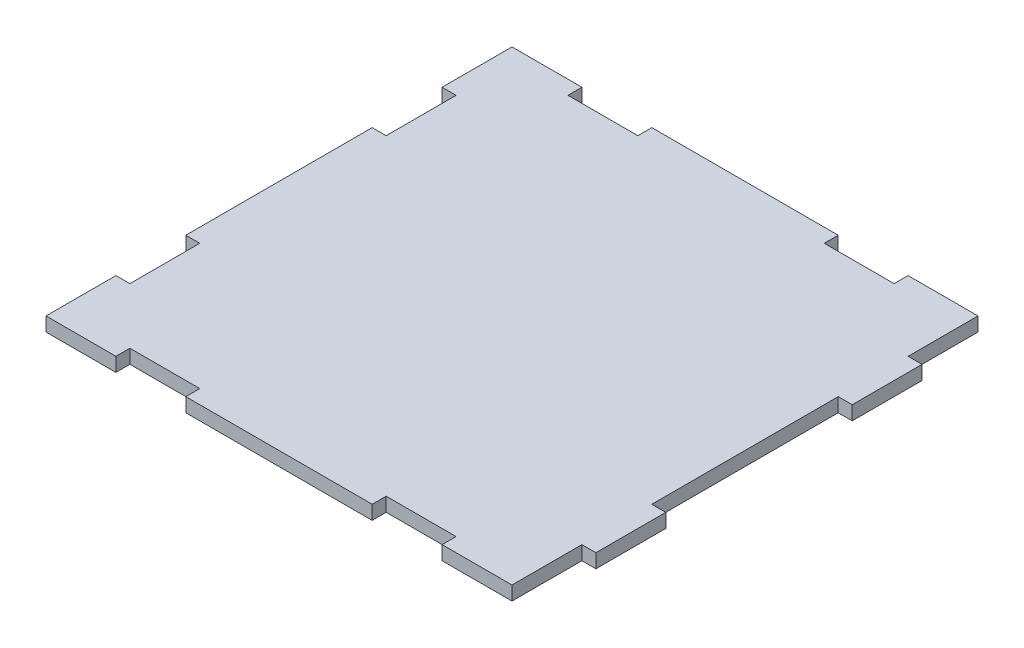
SolidWorks part; units mm, degrees
ref_plane "Plano frontal" through (0, 0, 0) normal (0, 0, 1) x (1, 0, 0)
ref_plane "Plano superior" through (0, 0, 0) normal (0, 1, 0) x (1, 0, 0)
ref_plane "Plano direito" through (0, 0, 0) normal (1, 0, 0) x (0, 0, -1)
sketch "Esboço1" plane through (0, 0, 0) normal (0, 1, 0) x (1, 0, 0)
  line L0 (100, 70) -> (100, 100)
  line L1 (-100, -100) -> (100, -100)
  line L2 (-100, -100) -> (-100, 100)
  line L3 (-100, 100) -> (100, 100)
  line L5 (-100, -100) -> (100, 100) construction
  line L6 (-100, 100) -> (100, -100) construction
  line L7 (100, 70) -> (106, 70)
  line L9 (100, 40) -> (106, 40)
  line L10 (106, 70) -> (106, 40)
  line L11 (100, -40) -> (106, -40)
  line L13 (100, -70) -> (106, -70)
  line L14 (106, -40) -> (106, -70)
  line L15 (100, 40) -> (100, -40)
  line L16 (100, -70) -> (100, -100)
  point P0 (0, 0)
  dimension "D1" = 200
  dimension "D2" = 200
  dimension "D3" = 6
  dimension "D4" = 6
  dimension "D5" = 30
  dimension "D6" = 30
  dimension "D7" = 30
  dimension "D8" = 30
  dimension "D9" = 6
  dimension "D10" = 6
extrude "Ressalto-extrusão1" add sketch "Esboço1" along normal blind 6
sketch "Esboço2" plane through (0, 6, 0) normal (0, 1, 0) x (1, 0, 0)
  line L0 (-100, -100) -> (100, -100) construction
  line L1 (-70, -100) -> (-40, -100)
  line L2 (-70, -100) -> (-70, -94)
  line L3 (-70, -94) -> (-40, -94)
  line L4 (-40, -100) -> (-40, -94)
  line L6 (40, -100) -> (70, -100)
  line L7 (40, -100) -> (40, -94)
  line L8 (40, -94) -> (70, -94)
  line L9 (70, -100) -> (70, -94)
  line L10 (-100, 100) -> (-100, -100) construction
  line L11 (100, 100) -> (-100, 100) construction
  line L12 (-70, 100) -> (-40, 100)
  line L13 (-70, 100) -> (-70, 94)
  line L14 (-70, 94) -> (-40, 94)
  line L15 (-40, 100) -> (-40, 94)
  line L16 (100, 70) -> (100, 100) construction
  line L17 (40, 100) -> (70, 100)
  line L18 (40, 100) -> (40, 94)
  line L19 (40, 94) -> (70, 94)
  line L20 (70, 100) -> (70, 94)
  line L21 (-100, 70) -> (-94, 70)
  line L22 (-100, 70) -> (-100, 40)
  line L23 (-100, 40) -> (-94, 40)
  line L24 (-94, 70) -> (-94, 40)
  line L25 (-100, -40) -> (-94, -40)
  line L26 (-100, -40) -> (-100, -70)
  line L27 (-100, -70) -> (-94, -70)
  line L28 (-94, -40) -> (-94, -70)
  line L29 (100, -100) -> (100, -70) construction
  dimension "D1" = 30
  dimension "D2" = 30
  dimension "D3" = 6
  dimension "D4" = 6
  dimension "D5" = 30
  dimension "D6" = 30
  dimension "D7" = 30
  dimension "D8" = 30
  dimension "D9" = 30
  dimension "D10" = 6
  dimension "D11" = 30
  dimension "D12" = 6
  dimension "D13" = 6
  dimension "D14" = 6
  dimension "D15" = 30
  dimension "D16" = 30
  dimension "D17" = 30
  dimension "D18" = 30
extrude "Corte-extrusão1" cut sketch "Esboço2" against normal blind 10
